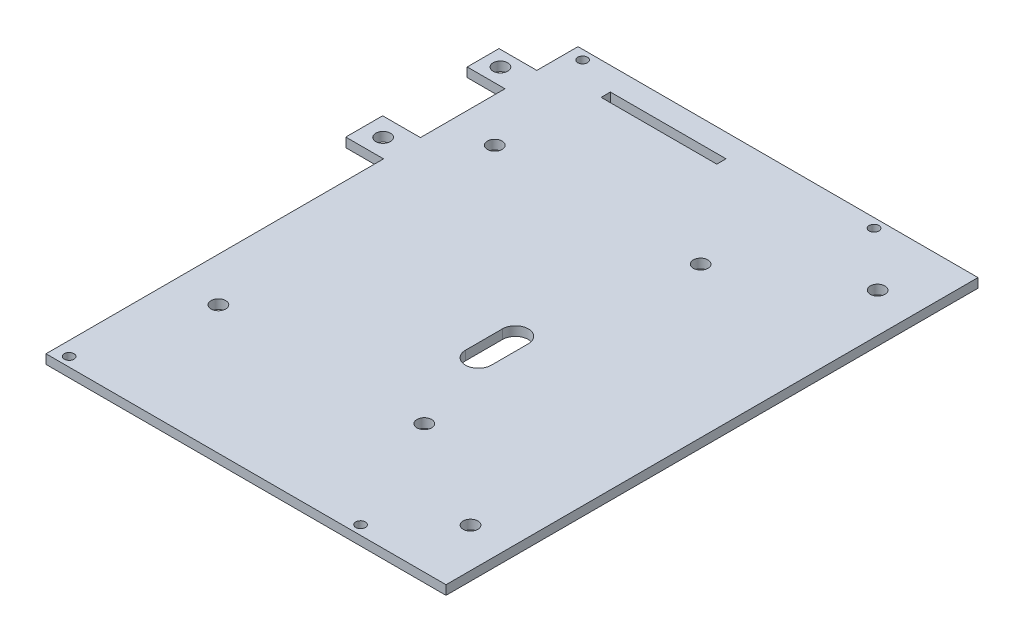
SolidWorks part; units mm, degrees
ref_plane "前视基准面" through (0, 0, 0) normal (0, 0, 1) x (1, 0, 0)
ref_plane "上视基准面" through (0, 0, 0) normal (0, 1, 0) x (1, 0, 0)
ref_plane "右视基准面" through (0, 0, 0) normal (1, 0, 0) x (0, 0, -1)
sketch "草图1" plane through (0, 0, 0) normal (0, 1, 0) x (1, 0, 0)
  line L0 (-8.17, -15.78) -> (0, -15.78) construction
  line L1 (0, 0) -> (86.47, 0)
  line L2 (0, 0) -> (0, -115)
  line L3 (0, -115) -> (86.47, -115)
  line L4 (86.47, 0) -> (86.47, -115)
  line L5 (5.05, -23.04) -> (58.39, -23.04) construction
  line L6 (5.05, -23.04) -> (5.05, -91.62) construction
  line L7 (5.05, -91.62) -> (58.39, -91.62) construction
  line L8 (58.39, -23.04) -> (58.39, -91.62) construction
  line L9 (9.47, -27.46) -> (53.97, -27.46) construction
  line L10 (9.47, -27.46) -> (9.47, -87.2) construction
  line L11 (9.47, -87.2) -> (53.97, -87.2) construction
  line L12 (53.97, -27.46) -> (53.97, -87.2) construction
  line L13 (86.47, -8.9) -> (-12.83, -8.9) construction
  line L14 (86.47, -8.9) -> (86.47, -105.5) construction
  line L15 (86.47, -105.5) -> (-12.83, -105.5) construction
  line L16 (-12.83, -8.9) -> (-12.83, -105.5) construction
  line L17 (-8.17, -8.9) -> (0, -8.9) construction
  line L18 (-8.17, -8.9) -> (-8.17, -42.03) construction
  line L19 (-8.17, -42.03) -> (0, -42.03) construction
  line L20 (0, -8.9) -> (0, -42.03) construction
  line L21 (-8.17, -34.06) -> (0, -34.06) construction
  line L22 (47.47, -61) -> (47.47, -69) construction
  line L23 (1, 0) -> (68, 0) construction
  line L24 (1, 0) -> (1, -115) construction
  line L25 (1, -115) -> (68, -115) construction
  line L26 (68, 0) -> (68, -115) construction
  line L27 (3, -2) -> (66, -2) construction
  line L28 (3, -2) -> (3, -113) construction
  line L29 (3, -113) -> (66, -113) construction
  line L30 (66, -2) -> (66, -113) construction
  line L31 (-8.17, -8.9) -> (0, -8.9)
  line L32 (-8.17, -8.9) -> (-8.17, -15.78)
  line L33 (-8.17, -15.78) -> (0, -15.78)
  line L34 (0, -8.9) -> (0, -15.78)
  line L35 (-8.17, -34.06) -> (0, -34.06)
  line L36 (-8.17, -34.06) -> (-8.17, -42.03)
  line L37 (-8.17, -42.03) -> (0, -42.03)
  line L38 (0, -34.06) -> (0, -42.03)
  line L51 (50.27, -61) -> (50.27, -69)
  line L52 (44.67, -61) -> (44.67, -69)
  line L54 (12, -5) -> (37, -5)
  line L55 (12, -5) -> (12, -7)
  line L56 (12, -7) -> (37, -7)
  line L57 (37, -5) -> (37, -7)
  circle A0 centre (9.47, -27.46) radius 1.585
  circle A1 centre (53.97, -27.46) radius 1.585
  circle A2 centre (9.47, -87.2) radius 1.585
  circle A3 centre (53.97, -87.2) radius 1.585
  circle A4 centre (77.97, -13.2) radius 1.585
  circle A5 centre (77.97, -101.2) radius 1.585
  circle A6 centre (-4.57, -12.2) radius 1.585
  circle A7 centre (-4.07, -38.06) radius 1.585
  circle A8 centre (3, -2) radius 1.05
  circle A9 centre (66, -2) radius 1.05
  circle A10 centre (3, -113) radius 1.05
  circle A11 centre (66, -113) radius 1.05
  arc A16 (50.27, -61) -> (44.67, -61) centre (47.47, -61) ccw
  arc A17 (44.67, -69) -> (50.27, -69) centre (47.47, -69) ccw
  point P49 (47.47, -65)
  dimension "D11" = 3.17
  dimension "D12" = 3.17
  dimension "D13" = 3.17
  dimension "D14" = 3.17
  dimension "D19" = 3.17
  dimension "D22" = 3.17
  dimension "D30" = 3.17
  dimension "D33" = 3.17
  dimension "D42" = 2.1
  dimension "D43" = 2.1
  dimension "D44" = 2.1
  dimension "D45" = 2.1
  dimension "D52" = 5
  dimension "D53" = 2
  dimension "D2" = 115
  dimension "D3" = 53.34
  dimension "D4" = 68.58
  dimension "D5" = 4.42
  dimension "D6" = 4.42
  dimension "D7" = 4.42
  dimension "D8" = 4.42
  dimension "D9" = 99.3
  dimension "D10" = 96.6
  dimension "D15" = 68.5
  dimension "D16" = 74
  dimension "D17" = 18.3
  dimension "D18" = 22.3
  dimension "D20" = 68.5
  dimension "D21" = 14
  dimension "D23" = 94.64
  dimension "D24" = 8.17
  dimension "D25" = 6.88
  dimension "D26" = 18.28
  dimension "D27" = 7.97
  dimension "D28" = 3.6
  dimension "D29" = 3.3
  dimension "D31" = 4.1
  dimension "D32" = 4
  dimension "D34" = 9.5
  dimension "D35" = 2
  dimension "D36" = 2
  dimension "D37" = 2
  dimension "D38" = 2
  dimension "D39" = 67
  dimension "D40" = 115
  dimension "D41" = 1
  dimension "D46" = 5.6
  dimension "D47" = 8
  dimension "D48" = 46
  dimension "D49" = 39
  dimension "D50" = 12
  dimension "D51" = 25
extrude "凸台-拉伸1" add sketch "草图1" along normal blind 2
